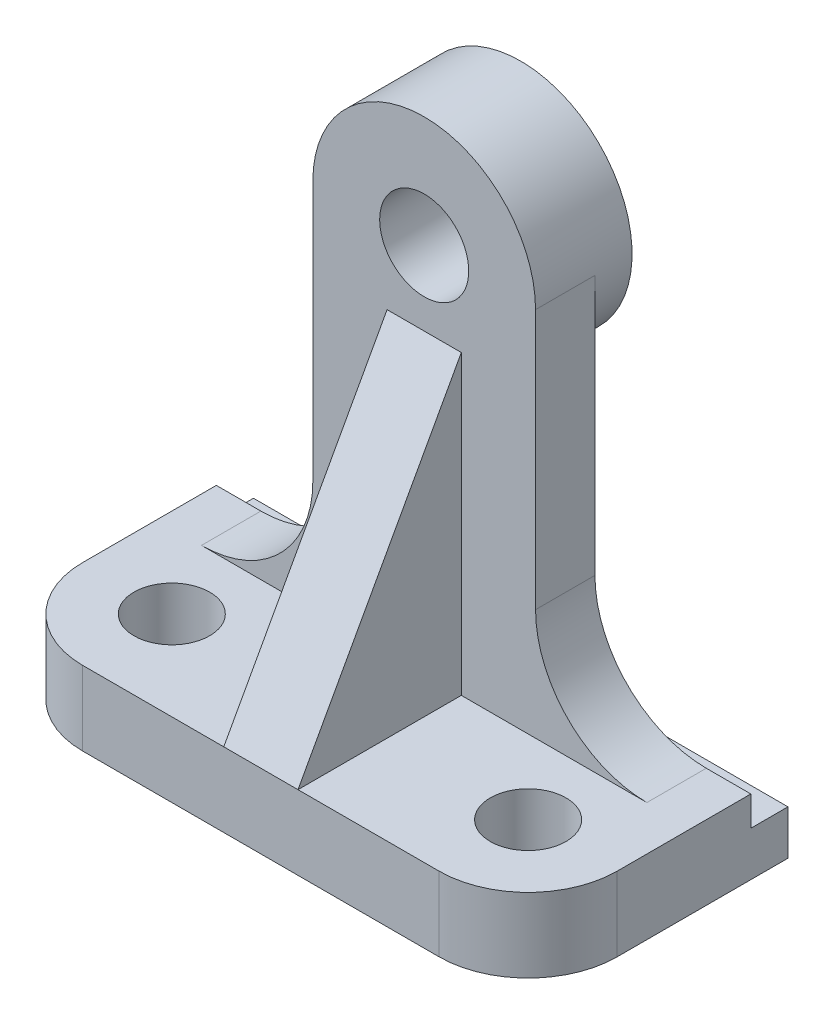
SolidWorks part; units mm, degrees
ref_plane "Front Plane" through (0, 0, 0) normal (0, 0, 1) x (1, 0, 0)
ref_plane "Top Plane" through (0, 0, 0) normal (0, 1, 0) x (1, 0, 0)
ref_plane "Right Plane" through (0, 0, 0) normal (1, 0, 0) x (0, 0, -1)
sketch "Sketch1" plane through (0, 0, 0) normal (0, 1, 0) x (1, 0, 0)
  line L1 (36, 17.5) -> (-36, 17.5)
  line L2 (36, 17.5) -> (36, -5.5)
  line L3 (24, -17.5) -> (-24, -17.5)
  line L4 (-36, 17.5) -> (-36, -5.5)
  line L5 (36, 17.5) -> (-36, -17.5) construction
  line L6 (36, -17.5) -> (-36, 17.5) construction
  arc A0 (36, -5.5) -> (24, -17.5) centre (24, -5.5) cw
  arc A1 (-24, -17.5) -> (-36, -5.5) centre (-24, -5.5) cw
  circle A2 centre (-24, -5.5) radius 5.1
  circle A3 centre (24, -5.5) radius 5.1
  point P0 (0, 0)
  point P14 (0, 0)
  dimension "D3" = 12
  dimension "D4" = 10.2
  dimension "D1" = 35
  dimension "D2" = 72
extrude "Boss-Extrude1" add sketch "Sketch1" along normal blind 10
cosmetic thread "Cosmetic Thread1" parameters "D1"=6, "D2"=12
cosmetic thread "Cosmetic Thread2" parameters "D1"=6, "D2"=12
sketch "Sketch2" plane through (-36, 0, 0) normal (-1, 0, 0) x (0, 0, 1)
  line L1 (-17.5, 10) -> (-12.5, 10)
  line L2 (-17.5, 10) -> (-17.5, 6)
  line L3 (-17.5, 6) -> (-12.5, 6)
  line L4 (-12.5, 10) -> (-12.5, 6)
  dimension "D1" = 5
  dimension "D2" = 4
extrude "Cut-Extrude1" cut sketch "Sketch2" against normal through all
sketch "Sketch3" plane through (0, 0, -12.5) normal (0, 0, -1) x (-1, 0, 0)
  line L0 (0, 10) -> (0, 60) construction
  line L1 (-36, 10) -> (36, 10) construction
  line L2 (-15, 60) -> (-15, 25)
  line L3 (15, 60) -> (15, 25)
  line L6 (-30, 10) -> (30, 10)
  circle A0 centre (0, 60) radius 6
  arc A1 (15, 60) -> (-15, 60) centre (0, 60) ccw
  arc A2 (15, 25) -> (30, 10) centre (30, 25) ccw
  arc A3 (-15, 25) -> (-30, 10) centre (-30, 25) cw
  point P17 (15, 10)
  point P20 (-15, 10)
  dimension "D2" = 12
  dimension "D3" = 30
  dimension "D4" = 15
  dimension "D1" = 50
extrude "Boss-Extrude2" add sketch "Sketch3" against normal blind 8
sketch "Sketch4" plane through (0, 0, -12.5) normal (0, 0, -1) x (-1, 0, 0)
  line L3 (-15, 60) -> (-15, 25)
  line L4 (15, 25) -> (15, 60)
  line L5 (-30, 10) -> (30, 10)
  line L6 (-15, 60) -> (-15, 25)
  line L7 (15, 25) -> (15, 60)
  line L8 (-30, 10) -> (30, 10)
  circle A0 centre (0, 60) radius 15
  circle A2 centre (0, 60) radius 6
  circle A3 centre (0, 60) radius 6
  arc A6 (15, 60) -> (-15, 60) centre (0, 60) ccw
  arc A7 (15, 25) -> (30, 10) centre (30, 25) ccw
  arc A8 (-30, 10) -> (-15, 25) centre (-30, 25) ccw
  arc A9 (15, 60) -> (-15, 60) centre (0, 60) ccw
  arc A10 (15, 25) -> (30, 10) centre (30, 25) ccw
  arc A11 (-30, 10) -> (-15, 25) centre (-30, 25) ccw
  arc M5 (15, 60) -> (-15, 60) centre (0, 60) ccw
  circle M11 centre (0, 60) radius 6
  dimension "D1" = 0
  dimension "D2" = 0
extrude "Boss-Extrude4" add sketch "Sketch4" along normal blind 5 contours A0 M5 M11
sketch "Sketch7" plane through (0, 0, 0) normal (1, 0, 0) x (0, 0, -1)
  line L0 (-17.5, 10) -> (4.5, 50)
  line L1 (4.5, 60) -> (4.5, 25) construction
  line L2 (-5.5, 10) -> (12.5, 10) construction
  dimension "D1" = 40
rib "Rib1" sketch "Sketch7" sketch "Sketch7" thickness 10 extrusion direction parallel to sketch draft on no parameters "D1"=10
